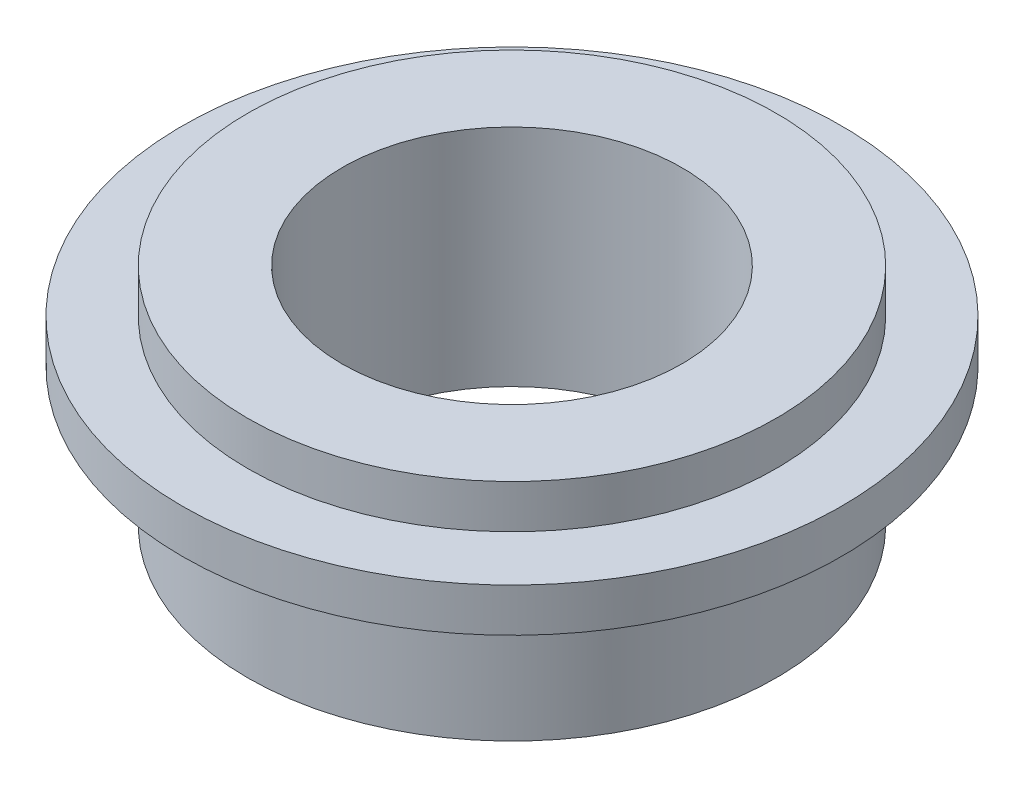
SolidWorks part; units mm, degrees
ref_plane "Plano frontal" through (0, 0, 0) normal (0, 0, 1) x (1, 0, 0)
ref_plane "Plano superior" through (0, 0, 0) normal (0, 1, 0) x (1, 0, 0)
ref_plane "Plano direito" through (0, 0, 0) normal (1, 0, 0) x (0, 0, -1)
sketch "Esboço3" plane through (0, 0, 0) normal (0, 0, 1) x (1, 0, 0)
  line L0 (0, 11.544) -> (0, -10.5274) construction
  line L1 (-18.2205, -9.9458) -> (-11.7205, -9.9458)
  line L2 (-11.7205, 5.5542) -> (-18.2205, 5.5542)
  line L3 (-18.2205, 5.5542) -> (-18.2205, 2.5542)
  line L4 (-18.2205, 2.5542) -> (-22.7205, 2.5542)
  line L5 (-22.7205, 2.5542) -> (-22.7205, 1.0542)
  line L6 (-22.7205, 1.0542) -> (-18.2205, 1.0542)
  line L7 (-18.2205, 1.0542) -> (-18.2205, -9.9458)
  line L8 (-11.7205, -9.9458) -> (-11.7205, 5.5542)
  dimension "D1" = 3
  dimension "D2" = 6.5
  dimension "D3" = 1.5
  dimension "D4" = 11
  dimension "D5" = 4.5
revolve "Revolução2" add sketch "Esboço3" angle 360 about L0
sketch "Esboço6" plane through (0, 1.0542, 0) normal (0, -1, 0) x (1, 0, 0)
  circle A0 centre (0, 0) radius 18.2205 construction
  circle A1 centre (0, 0) radius 22.7205
  circle A2 centre (0, 0) radius 22.7205
  circle A3 centre (0, 0) radius 18.2205
  dimension "D1" = 0
extrude "Ressalto-extrusão4" add sketch "Esboço6" along normal blind 1.5
